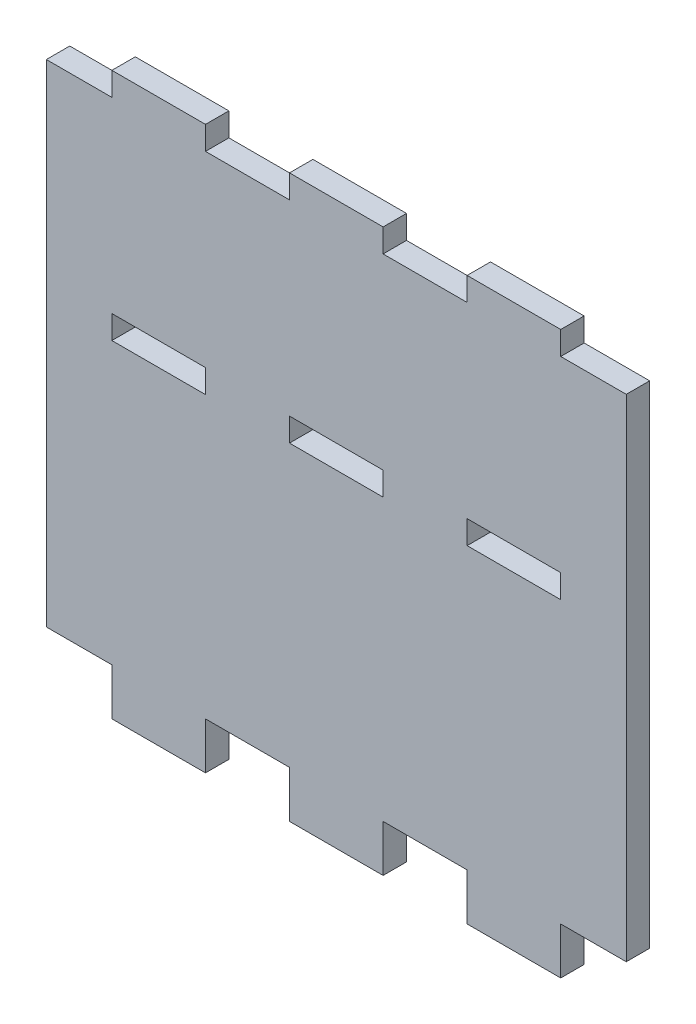
SolidWorks part; units mm, degrees
material "Beech"
ref_plane "Front" through (0, 0, 0) normal (0, 0, 1) x (1, 0, 0)
ref_plane "Top" through (0, 0, 0) normal (0, 1, 0) x (1, 0, 0)
ref_plane "Right" through (0, 0, 0) normal (1, 0, 0) x (0, 0, -1)
sketch "Sketch1" plane through (0, 0, 0) normal (0, 0, 1) x (1, 0, 0)
  line L0 (0, -5.7498) -> (0, 4.0531) construction
  line L1 (-30.975, -30) -> (30.975, -30) construction
  line L2 (-30.975, -30) -> (-30.975, 30) construction
  line L3 (-30.975, 30) -> (30.975, 30) construction
  line L4 (30.975, -30) -> (30.975, 30) construction
  line L5 (-30.975, -30) -> (30.975, 30) construction
  line L6 (-30.975, 30) -> (30.975, -30) construction
  line L12 (-23.975, 30) -> (-23.975, 27.5)
  line L14 (-13.975, 27.5) -> (-13.975, 30)
  line L16 (-5, 30) -> (-5, 27.5)
  line L18 (5, 27.5) -> (5, 30)
  line L20 (13.975, 30) -> (13.975, 27.5)
  line L22 (23.975, 27.5) -> (23.975, 30)
  line L24 (8.5799, 0) -> (-10.6488, 0) construction
  line L26 (23.975, -25) -> (23.975, -30)
  line L28 (13.975, -30) -> (13.975, -25)
  line L30 (5, -25) -> (5, -30)
  line L32 (-5, -30) -> (-5, -25)
  line L34 (-13.975, -25) -> (-13.975, -30)
  line L36 (-23.975, -30) -> (-23.975, -25)
  line L38 (-5, 7.5) -> (5, 7.5)
  line L39 (13.975, 5) -> (23.975, 5)
  line L40 (13.975, 5) -> (13.975, 7.5)
  line L41 (13.975, 7.5) -> (23.975, 7.5)
  line L42 (23.975, 5) -> (23.975, 7.5)
  line L43 (13.975, 5) -> (23.975, 7.5) construction
  line L44 (13.975, 7.5) -> (23.975, 5) construction
  line L45 (5, 5) -> (5, 7.5)
  line L46 (-5, 5) -> (5, 5)
  line L47 (-5, 5) -> (-5, 7.5)
  line L48 (-23.975, 7.5) -> (-13.975, 7.5)
  line L49 (-13.975, 5) -> (-13.975, 7.5)
  line L50 (-23.975, 5) -> (-13.975, 5)
  line L51 (-23.975, 5) -> (-23.975, 7.5)
  line L54 (-30.975, 27.5) -> (-23.975, 27.5)
  line L55 (-23.975, 30) -> (-13.975, 30)
  line L56 (-13.975, 27.5) -> (-5, 27.5)
  line L57 (-5, 30) -> (5, 30)
  line L58 (5, 27.5) -> (13.975, 27.5)
  line L59 (13.975, 30) -> (23.975, 30)
  line L60 (23.975, 27.5) -> (30.975, 27.5)
  line L61 (-30.975, -25) -> (-23.975, -25)
  line L62 (-23.975, -30) -> (-13.975, -30)
  line L63 (-13.975, -25) -> (-5, -25)
  line L64 (-5, -30) -> (5, -30)
  line L65 (5, -25) -> (13.975, -25)
  line L66 (13.975, -30) -> (23.975, -30)
  line L67 (23.975, -25) -> (30.975, -25)
  line L68 (30.975, 27.5) -> (30.975, -25)
  line L69 (-30.975, 27.5) -> (-30.975, -25)
  point P0 (0, 0)
  point P34 (18.975, 6.25)
  dimension "D1" = 61.95
  dimension "D2" = 60
  dimension "D3" = 7
  dimension "D4" = 5
  dimension "D5" = 10
  dimension "D6" = 10
  dimension "D7" = 5
  dimension "D9" = 14
  dimension "D10" = 10
  dimension "D11" = 35
  dimension "D8" = 3
extrude "Boss-Extrude1" add sketch "Sketch1" along normal blind 2.5
